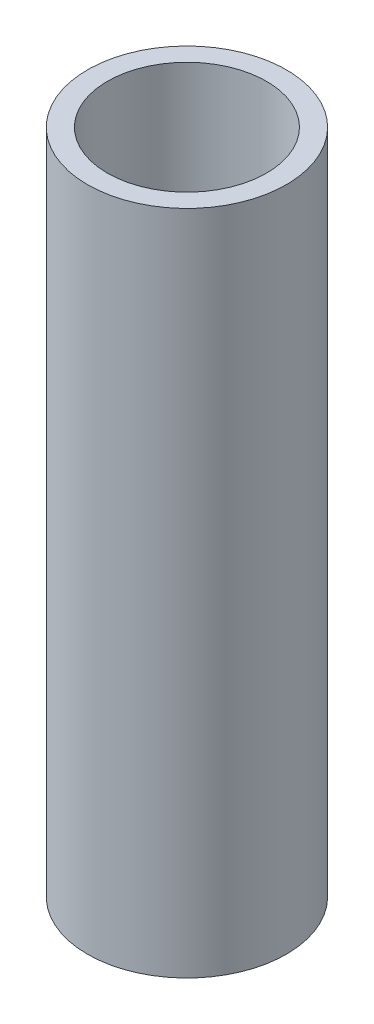
SolidWorks part; units mm, degrees
material "PE High Density"
ref_plane "Front Plane" through (0, 0, 0) normal (0, 0, 1) x (1, 0, 0)
ref_plane "Top Plane" through (0, 0, 0) normal (0, 1, 0) x (1, 0, 0)
ref_plane "Right Plane" through (0, 0, 0) normal (1, 0, 0) x (0, 0, -1)
sketch "Sketch1" plane through (0, 0, 0) normal (0, 1, 0) x (1, 0, 0)
  circle A0 centre (0, 0) radius 50
  circle A1 centre (0, 0) radius 40
  dimension "D1" = 100
  dimension "D2" = 80
extrude "Boss-Extrude1" add sketch "Sketch1" along normal blind 335
scale "Scale1" scale about centroid uniform scaling yes scale factor 0.75
